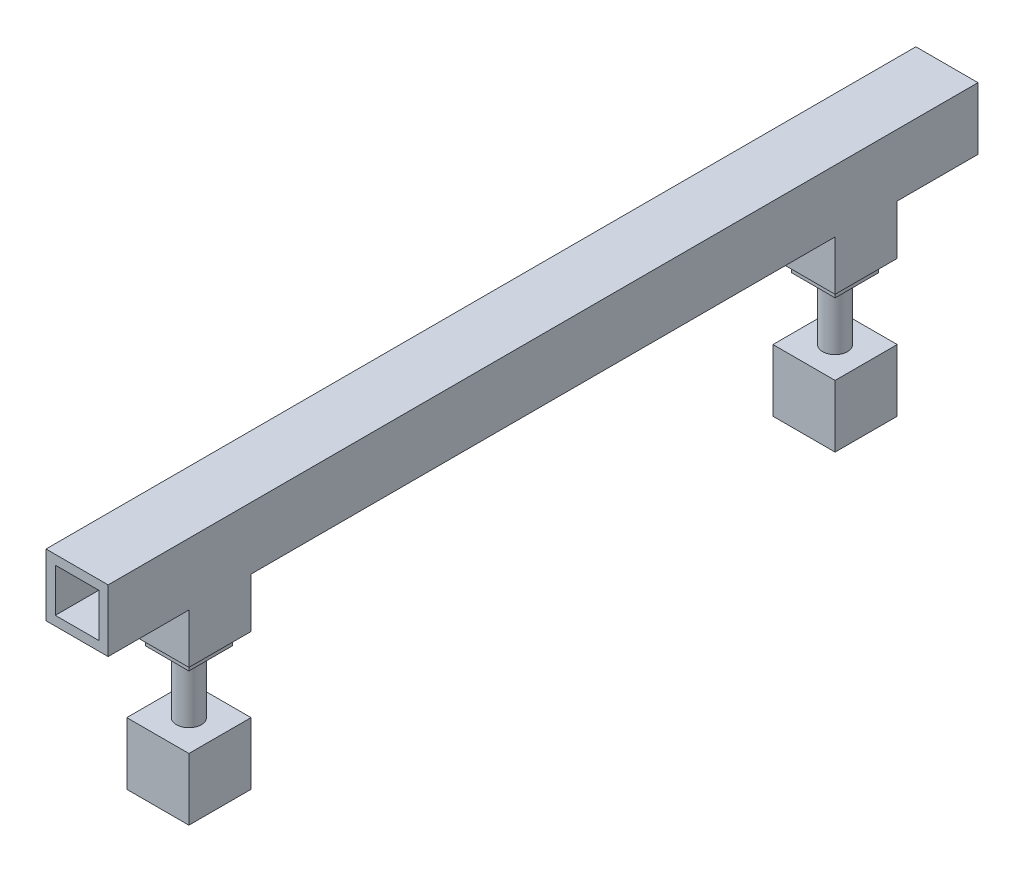
SolidWorks part; units mm, degrees
ref_plane "Спереди" through (0, 0, 0) normal (0, 0, 1) x (1, 0, 0)
ref_plane "Сверху" through (0, 0, 0) normal (0, 1, 0) x (1, 0, 0)
ref_plane "Справа" through (0, 0, 0) normal (1, 0, 0) x (0, 0, -1)
sketch "Эскиз1" plane through (0, 0, 0) normal (0, 0, 1) x (1, 0, 0)
  line L1 (-25, -25) -> (25, -25)
  line L2 (-25, -25) -> (-25, 25)
  line L3 (-25, 25) -> (25, 25)
  line L4 (25, -25) -> (25, 25)
  line L5 (-25, -25) -> (25, 25) construction
  line L6 (-25, 25) -> (25, -25) construction
  line L7 (-17.5, -17.5) -> (17.5, -17.5)
  line L8 (-17.5, -17.5) -> (-17.5, 17.5)
  line L9 (-17.5, 17.5) -> (17.5, 17.5)
  line L10 (17.5, -17.5) -> (17.5, 17.5)
  line L11 (-17.5, -17.5) -> (17.5, 17.5) construction
  line L12 (-17.5, 17.5) -> (17.5, -17.5) construction
  point P0 (0, 0)
  point P7 (0, 0)
  dimension "D1" = 50
  dimension "D2" = 35
extrude "Бобышка-Вытянуть1" add sketch "Эскиз1" along normal mid plane 700
sketch "Эскиз2" plane through (0, -25, 0) normal (0, -1, 0) x (1, 0, 0)
  line L0 (0, 0) -> (25, 0) construction
  line L1 (25, 350) -> (25, -350) construction
  line L2 (-25, -235) -> (25, -235)
  line L3 (-25, 235) -> (25, 235)
  line L4 (-25, 235) -> (-25, 285)
  line L5 (-25, 285) -> (25, 285)
  line L6 (25, 235) -> (25, 285)
  line L7 (-25, 235) -> (25, 285) construction
  line L8 (-25, 285) -> (25, 235) construction
  line L9 (25, -235) -> (25, -285)
  line L10 (-25, -235) -> (-25, -285)
  line L11 (-25, -285) -> (25, -285)
  line L12 (17.5, -242.5) -> (17.5, -277.5)
  line L13 (-17.5, 242.5) -> (17.5, 242.5)
  line L14 (-17.5, 242.5) -> (-17.5, 277.5)
  line L15 (-17.5, 277.5) -> (17.5, 277.5)
  line L16 (17.5, 242.5) -> (17.5, 277.5)
  line L17 (-17.5, 242.5) -> (17.5, 277.5) construction
  line L18 (-17.5, 277.5) -> (17.5, 242.5) construction
  line L19 (-17.5, -242.5) -> (17.5, -242.5)
  line L20 (-17.5, -242.5) -> (-17.5, -277.5)
  line L21 (-17.5, -277.5) -> (17.5, -277.5)
  point P5 (0, 260)
  point P14 (0, 260)
  dimension "D1" = 50
  dimension "D2" = 260
  dimension "D3" = 35
extrude "Бобышка-Вытянуть2" add sketch "Эскиз2" along normal blind 40
sketch "Эскиз3" plane through (0, -65, 0) normal (0, -1, 0) x (1, 0, 0)
  line L0 (-17.5, 242.5) -> (17.5, 242.5) construction
  line L1 (17.5, 242.5) -> (17.5, 277.5) construction
  line L2 (17.5, 277.5) -> (-17.5, 277.5) construction
  line L3 (-17.5, 277.5) -> (-17.5, 242.5) construction
  line L4 (-17.5, 242.5) -> (17.5, 242.5)
  line L5 (17.5, 242.5) -> (17.5, 277.5)
  line L6 (17.5, 277.5) -> (-17.5, 277.5)
  line L7 (-17.5, 277.5) -> (-17.5, 242.5)
  line L8 (0, 0) -> (114.7928, 0) construction
  line L9 (17.5, -242.5) -> (17.5, -277.5)
  line L10 (-17.5, -242.5) -> (17.5, -242.5)
  line L11 (-17.5, -277.5) -> (-17.5, -242.5)
  line L12 (17.5, -277.5) -> (-17.5, -277.5)
extrude "Вырез-Вытянуть1" cut sketch "Эскиз3" against normal blind 70
sketch "Эскиз4" plane through (0, -65, 0) normal (0, -1, 0) x (1, 0, 0)
  line L0 (25, 235) -> (25, 285) construction
  line L1 (-25, 350) -> (25, 350) construction
  line L2 (-17.5, 277.5) -> (-17.5, 242.5) construction
  line L3 (-17.5, 242.5) -> (17.5, 242.5) construction
  line L4 (17.5, 242.5) -> (17.5, 277.5) construction
  line L5 (17.5, 277.5) -> (-17.5, 277.5) construction
  line L6 (-17.5, 277.5) -> (-17.5, 242.5)
  line L7 (-17.5, 242.5) -> (17.5, 242.5)
  line L8 (17.5, 242.5) -> (17.5, 277.5)
  line L9 (17.5, 277.5) -> (-17.5, 277.5)
  line L10 (0, 0) -> (58.3014, 0) construction
  line L11 (-17.5, -277.5) -> (-17.5, -242.5)
  line L12 (-17.5, -242.5) -> (17.5, -242.5)
  line L13 (17.5, -277.5) -> (-17.5, -277.5)
  line L14 (17.5, -242.5) -> (17.5, -277.5)
  circle A0 centre (0, 260) radius 10
  circle A1 centre (0, -260) radius 10
  dimension "D1" = 20
  dimension "D2" = 25
  dimension "D3" = 90
extrude "Бобышка-Вытянуть3" add sketch "Эскиз4" along normal blind 10 separate body
sketch "Эскиз5" plane through (0, -75, 0) normal (0, -1, 0) x (1, 0, 0)
  line L0 (0, 0) -> (44.5832, 0) construction
  circle A0 centre (0, 260) radius 5
  circle A1 centre (0, 260) radius 10
  circle A2 centre (0, -260) radius 10
  circle A3 centre (0, -260) radius 5
  dimension "D1" = 10
  dimension "D2" = 20
extrude "Бобышка-Вытянуть4" add sketch "Эскиз5" along normal blind 50 separate body
sketch "Эскиз6" plane through (0, -125, 0) normal (0, -1, 0) x (1, 0, 0)
  line L0 (0, 0) -> (46.6834, 0) construction
  line L1 (25, 235) -> (-25, 235)
  line L2 (25, 235) -> (25, 285)
  line L3 (25, 285) -> (-25, 285)
  line L4 (-25, 235) -> (-25, 285)
  line L5 (25, 235) -> (-25, 285) construction
  line L6 (25, 285) -> (-25, 235) construction
  line L7 (25, -235) -> (25, -285)
  line L8 (25, -235) -> (-25, -235)
  line L9 (-25, -235) -> (-25, -285)
  line L10 (25, -285) -> (-25, -285)
  circle A0 centre (0, 260) radius 10 construction
  circle A1 centre (0, 260) radius 10
  circle A2 centre (0, -260) radius 10
  dimension "D1" = 50
extrude "Бобышка-Вытянуть5" add sketch "Эскиз6" along normal blind 50 separate body
